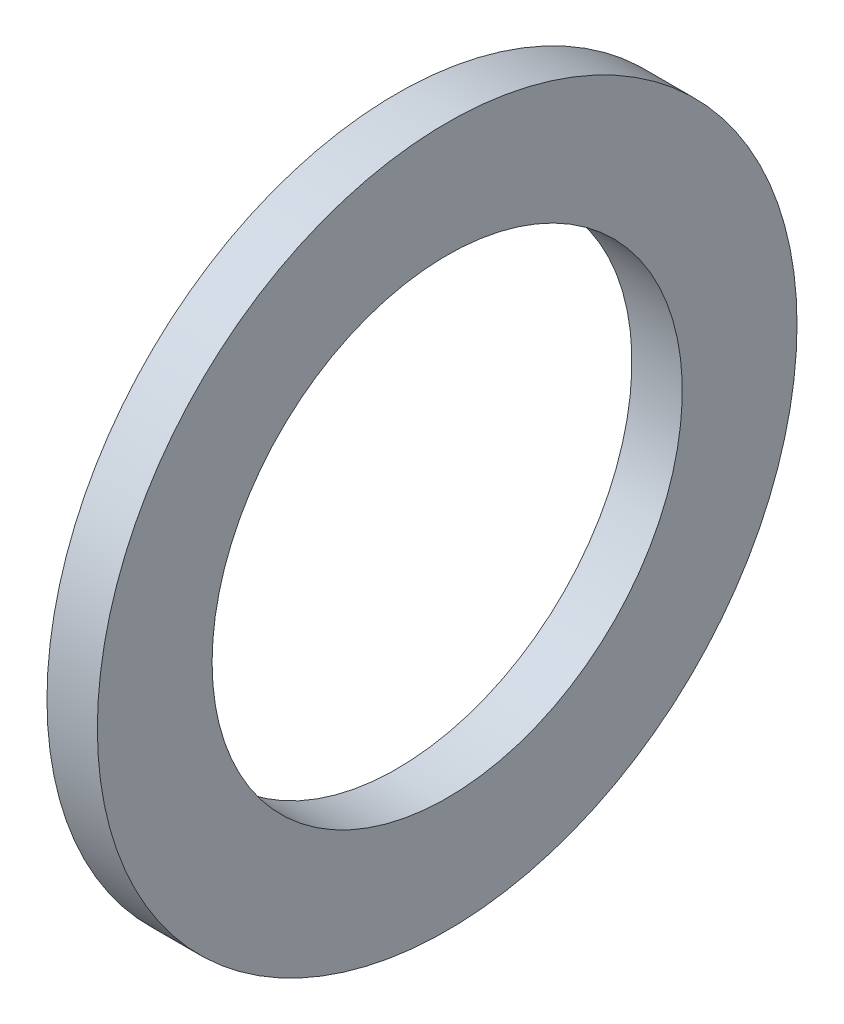
SolidWorks part; units mm, degrees
ref_plane "Plane1" through (0, 0, 0) normal (0, 0, 1) x (1, 0, 0)
ref_plane "Plane2" through (0, 0, 0) normal (0, 1, 0) x (1, 0, 0)
ref_plane "Plane3" through (0, 0, 0) normal (1, 0, 0) x (0, 0, -1)
sketch "Sketch1" plane through (0, 0, 0) normal (0, 0, 1) x (1, 0, 0)
  line L0 (-34.925, 0) -> (9.525, 0) construction
  line L1 (0, 84) -> (0, 125)
  line L2 (0, 125) -> (-18, 125)
  line L3 (-18, 125) -> (-18, 84)
  line L4 (-18, 84) -> (0, 84)
  dimension "Thickness" = 18
  dimension "Inside_dia" = 168
  dimension "Outside_dia" = 250
revolve "Base-Revolve" add sketch "Sketch1" angle 360 about L0
